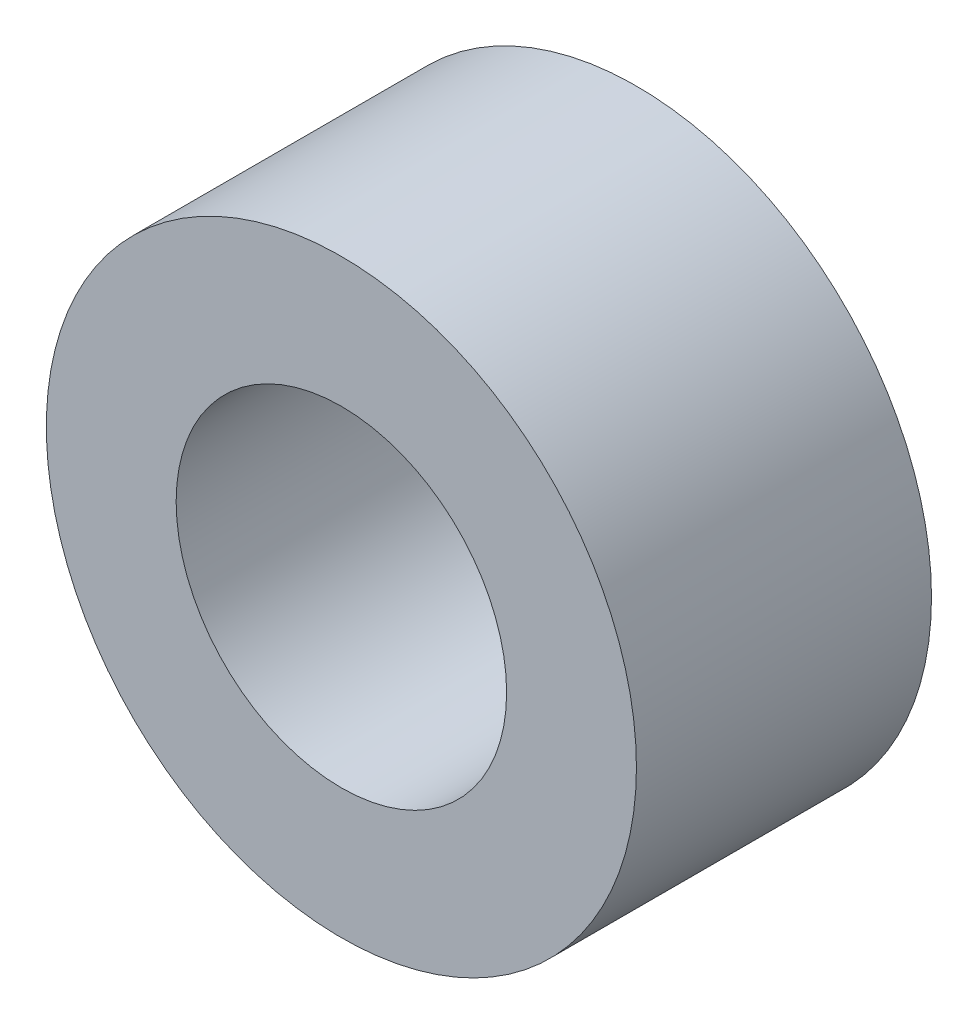
SolidWorks part; units mm, degrees
ref_plane "Front Plane" through (0, 0, 0) normal (0, 0, 1) x (1, 0, 0)
ref_plane "Top Plane" through (0, 0, 0) normal (0, 1, 0) x (1, 0, 0)
ref_plane "Right Plane" through (0, 0, 0) normal (1, 0, 0) x (0, 0, -1)
sketch "Sketch1" plane through (0, 0, 0) normal (0, 0, 1) x (1, 0, 0)
  circle A0 centre (0, 0) radius 3.175
  dimension "D1" = 6.35
extrude "Boss-Extrude1" add sketch "Sketch1" along normal blind 3.175
sketch "Sketch2" plane through (0, 0, 3.175) normal (0, 0, 1) x (1, 0, 0)
  circle A0 centre (0, 0) radius 1.778
  dimension "D1" = 3.556
extrude "Cut-Extrude1" cut sketch "Sketch2" against normal blind 3.175
